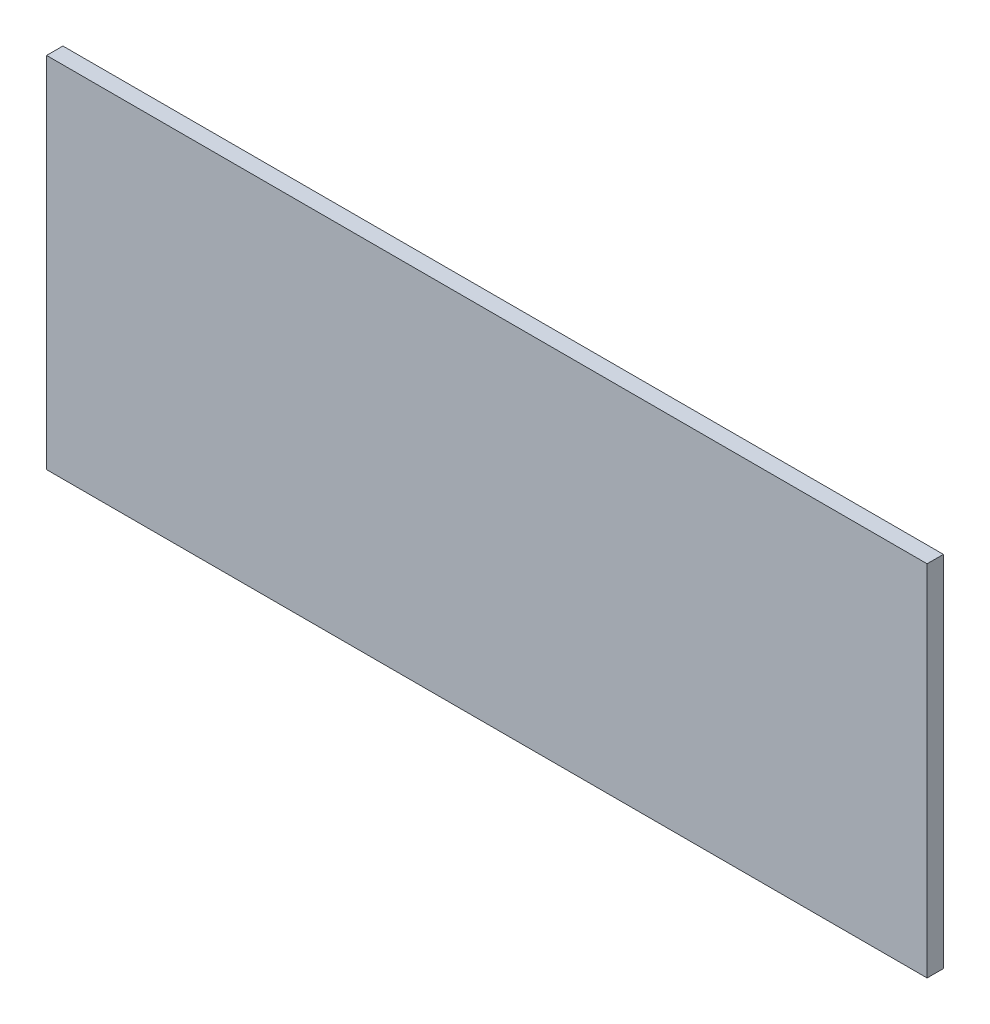
SolidWorks part; units mm, degrees
ref_plane "Front Plane" through (0, 0, 0) normal (1, 0, 0) x (0, 1, 0)
ref_plane "Top Plane" through (0, 0, 0) normal (0, 0, 1) x (0, 1, 0)
ref_plane "Right Plane" through (0, 0, 0) normal (0, 1, 0) x (-1, 0, 0)
sketch "Sketch1" plane through (0, 0, 0) normal (0, 0, 1) x (0, 1, 0)
  line L1 (0, 0) -> (110, 0)
  line L2 (0, 0) -> (0, 270)
  line L3 (0, 270) -> (110, 270)
  line L4 (110, 0) -> (110, 270)
  dimension "D1" = 270
  dimension "D2" = 110
extrude "Boss-Extrude1" add sketch "Sketch1" along normal blind 5 contours L2 L3 L4 L1
